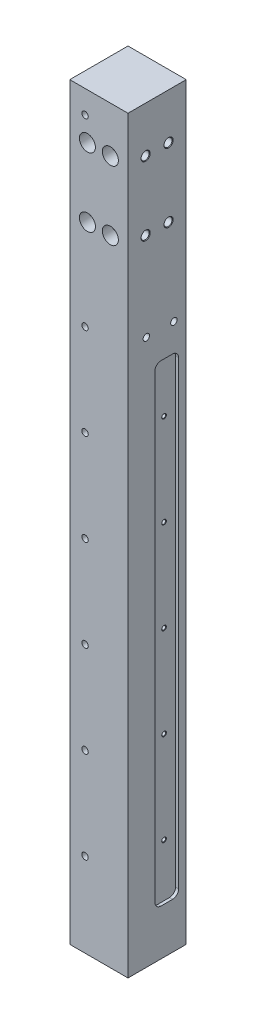
SolidWorks part; units mm, degrees
material "AISI 1045 Steel, cold drawn"
ref_plane "Front Plane" through (0, 0, 0) normal (0, 0, 1) x (1, 0, 0)
ref_plane "Top Plane" through (0, 0, 0) normal (0, 1, 0) x (1, 0, 0)
ref_plane "Right Plane" through (0, 0, 0) normal (1, 0, 0) x (0, 0, -1)
sketch "Sketch1" plane through (0, 0, 0) normal (0, 1, 0) x (1, 0, 0)
  line L1 (19.05, -19.05) -> (-19.05, -19.05)
  line L2 (19.05, -19.05) -> (19.05, 19.05)
  line L3 (19.05, 19.05) -> (-19.05, 19.05)
  line L4 (-19.05, -19.05) -> (-19.05, 19.05)
  line L5 (19.05, -19.05) -> (-19.05, 19.05) construction
  line L6 (19.05, 19.05) -> (-19.05, -19.05) construction
  point P0 (0, 0)
  dimension "D1" = 38.1
extrude "Boss-Extrude1" add sketch "Sketch1" along normal blind 490
ref_plane "Plane1" through (0, 0, 0) normal (-0.7071, 0, -0.7071) x (-0.7071, 0, 0.7071)
hole_wizard "CBORE for M5 SBHCS1" positions "Sketch2" profile "Sketch3" counterbore size "M5" standard "ANSI Metric" end condition through all
sketch "Sketch2" plane through (-19.05, 0, 0) normal (-1, 0, 0) x (0, 0, 1)
  line L0 (-7.5, 415) -> (7.5, 415) construction
  line L2 (-19.05, 490) -> (19.05, 490) construction
  line L3 (-7.5, 460) -> (7.5, 460) construction
  point P0 (-7.5, 415)
  point P2 (7.5, 415)
  point P9 (0, 415)
  point P13 (-7.5, 460)
  point P15 (7.5, 460)
  point P23 (0, 460)
  dimension "D1" = 75
  dimension "D2" = 15
  dimension "D3" = 30
sketch "Sketch3" plane through (-19.05, 415, -7.5) normal (0, 1, 0) x (0, 0, 1)
  line L0 (0, 0) -> (0, 38.1)
  line L1 (2.65, 37.75) -> (3, 38.1)
  line L2 (2.65, 37.75) -> (2.65, 32.85)
  line L3 (2.65, 32.85) -> (5.25, 32.85)
  line L4 (5.25, 32.85) -> (5.25, 0)
  line L5 (5.25, 0) -> (0, 0)
  line L11 (0, -6.35) -> (0, 107.95) construction
  line L12 (3, 38.1) -> (0, 38.1)
  line L13 (-2.65, 37.75) -> (-3, 38.1) construction
  dimension "Thru Hole Dia." = 5.3
  dimension "Thru Hole Depth" = 38.1
  dimension "C'Bore Dia." = 10.5
  dimension "C'Bore Depth" = 32.85
  dimension "Far C'Sink Dia." = 6
  dimension "Far C'Sink Angle" = 90
hole_wizard "M5x0.8 Tapped Hole1" positions "Sketch4" profile "Sketch6" tap size "M5x0.8" standard "ANSI Metric"
sketch "Sketch4" plane through (-19.05, 0, 0) normal (-1, 0, 0) x (0, 0, 1)
  line L0 (-19.05, 490) -> (19.05, 490) construction
  line L1 (19.05, 490) -> (19.05, 0) construction
  line L2 (9.05, 475) -> (9.05, 415) construction
  point P0 (9.05, 475)
  point P13 (9.05, 415)
  point P14 (9.05, 355)
  point P15 (9.05, 295)
  point P16 (9.05, 235)
  point P17 (9.05, 175)
  point P18 (9.05, 115)
  point P19 (9.05, 55)
  dimension "D1" = 15
  dimension "D2" = 10
  dimension "D4" = 60
  dimension "D3" = 8
sketch "Sketch6" plane through (-19.05, 475, 9.05) normal (0, 1, 0) x (0, 0, 1)
  line L0 (0, 0) -> (0, 9.6618)
  line L1 (0, 9.6618) -> (2.1, 8.4)
  line L2 (2.1, 8.4) -> (2.1, 0)
  line L5 (2.1, 0) -> (0, 0)
  line L10 (0, 9.6618) -> (-2.1, 8.4) construction
  line L11 (0, -6.35) -> (0, 107.95) construction
  dimension "Tap Drill Dia." = 4.2
  dimension "Tap Drill Depth" = 8.4
  dimension "Drill Angle" = 118
cosmetic thread "Hole Thread1" parameters "D1"=6, "D2"=5
cosmetic thread "Hole Thread2" parameters "D1"=6, "D2"=5
cosmetic thread "Hole Thread3" parameters "D1"=6, "D2"=5
cosmetic thread "Hole Thread4" parameters "D1"=6, "D2"=5
cosmetic thread "Hole Thread5" parameters "D1"=6, "D2"=5
cosmetic thread "Hole Thread6" parameters "D1"=6, "D2"=5
cosmetic thread "Hole Thread7" parameters "D1"=6, "D2"=5
hole_wizard "M5x0.8 Tapped Hole3" positions "Sketch9" profile "Sketch10" tap size "M5x0.8" standard "ANSI Metric"
sketch "Sketch9" plane through (19.05, 0, 0) normal (1, 0, 0) x (0, 0, -1)
  line L0 (10.95, 357) -> (-7.05, 357) construction
  line L2 (-19.05, 490) -> (-19.05, 0) construction
  line L3 (-19.05, 490) -> (19.05, 490) construction
  point P0 (-7.05, 357)
  point P2 (10.95, 357)
  point P9 (1.95, 357)
  dimension "D1" = 18
  dimension "D2" = 21
  dimension "D3" = 133
sketch "Sketch10" plane through (19.05, 357, 7.05) normal (0, 1, 0) x (0, 0, -1)
  line L0 (0, 0) -> (0, 7.6618)
  line L1 (0, 7.6618) -> (2.1, 6.4)
  line L2 (2.1, 6.4) -> (2.1, 0)
  line L5 (2.1, 0) -> (0, 0)
  line L10 (0, 7.6618) -> (-2.1, 6.4) construction
  line L11 (0, -6.35) -> (0, 107.95) construction
  dimension "Tap Drill Dia." = 4.2
  dimension "Tap Drill Depth" = 6.4
  dimension "Drill Angle" = 118
cosmetic thread "Hole Thread10" parameters "D1"=4, "D2"=5
cosmetic thread "Hole Thread11" parameters "D1"=4, "D2"=5
sketch "Sketch11" plane through (19.05, 0, 0) normal (1, 0, 0) x (0, 0, -1)
  line L1 (14.05, 339) -> (-1.45, 339)
  line L2 (14.05, 339) -> (14.05, 30)
  line L3 (14.05, 30) -> (-1.45, 30)
  line L4 (-1.45, 339) -> (-1.45, 30)
  line L5 (-19.05, 34.5) -> (19.05, 34.5) construction
  line L6 (-19.05, 490) -> (-19.05, 0) construction
  line L7 (19.05, 490) -> (19.05, 0) construction
  line L8 (-19.05, 0) -> (19.05, 0) construction
  dimension "D1" = 34.5
  dimension "D2" = 4.5
  dimension "D3" = 5
  dimension "D4" = 15.5
  dimension "D5" = 309
extrude "Cut-Extrude1" cut sketch "Sketch11" against normal blind 2
fillet "Fillet1" radius 4 4 edges at (18.05, 30, 1.45) (18.05, 30, -14.05) (18.05, 339, -14.05) (18.05, 339, 1.45)
hole_wizard "M3x0.5 Tapped Hole1" positions "Sketch12" profile "Sketch13" tap size "M3x0.5" standard "ANSI Metric"
sketch "Sketch12" plane through (17.05, 0, 0) normal (1, 0, 0) x (0, 0, -1)
  line L0 (19.05, 490) -> (19.05, 0) construction
  line L1 (-19.05, 0) -> (19.05, 0) construction
  line L2 (6.55, 64.5) -> (6.55, 124.5) construction
  point P0 (6.55, 64.5)
  point P15 (6.55, 124.5)
  point P16 (6.55, 184.5)
  point P17 (6.55, 244.5)
  point P18 (6.55, 304.5)
  dimension "D1" = 12.5
  dimension "D2" = 64.5
  dimension "D4" = 60
  dimension "D3" = 5
sketch "Sketch13" plane through (17.05, 64.5, -6.55) normal (0, 1, 0) x (0, 0, -1)
  line L0 (0, 0) -> (0, 8.2511)
  line L1 (0, 8.2511) -> (1.25, 7.5)
  line L2 (1.25, 7.5) -> (1.25, 0.275)
  line L3 (1.25, 0.275) -> (1.525, 0)
  line L5 (1.525, 0) -> (0, 0)
  line L6 (-1.25, 0.275) -> (-1.525, 0) construction
  line L10 (0, 8.2511) -> (-1.25, 7.5) construction
  line L11 (0, -6.35) -> (0, 107.95) construction
  dimension "Tap Drill Dia." = 2.5
  dimension "Tap Drill Depth" = 7.5
  dimension "Near C'Sink Dia." = 3.05
  dimension "Near C'Sink Angle" = 90
  dimension "Drill Angle" = 118
cosmetic thread "Hole Thread17" parameters "D1"=6, "D2"=3
cosmetic thread "Hole Thread18" parameters "D1"=6, "D2"=3
cosmetic thread "Hole Thread19" parameters "D1"=6, "D2"=3
cosmetic thread "Hole Thread20" parameters "D1"=6, "D2"=3
cosmetic thread "Hole Thread21" parameters "D1"=6, "D2"=3
mirror "Mirror2" about plane through (0, 0, 0) normal (-0.7071, 0, -0.7071) of "M3x0.5 Tapped Hole1", "Fillet1", "Cut-Extrude1", "M5x0.8 Tapped Hole3", "M5x0.8 Tapped Hole1", "CBORE for M5 SBHCS1"
cosmetic thread "Hole Thread22" parameters "D1"=6, "D2"=3
cosmetic thread "Hole Thread23" parameters "D1"=6, "D2"=3
cosmetic thread "Hole Thread24" parameters "D1"=6, "D2"=3
cosmetic thread "Hole Thread25" parameters "D1"=6, "D2"=5
cosmetic thread "Hole Thread26" parameters "D1"=6, "D2"=5
cosmetic thread "Hole Thread27" parameters "D1"=6, "D2"=3
cosmetic thread "Hole Thread28" parameters "D1"=4, "D2"=5
cosmetic thread "Hole Thread29" parameters "D1"=6, "D2"=5
cosmetic thread "Hole Thread30" parameters "D1"=6, "D2"=5
cosmetic thread "Hole Thread31" parameters "D1"=6, "D2"=3
cosmetic thread "Hole Thread32" parameters "D1"=6, "D2"=5
cosmetic thread "Hole Thread33" parameters "D1"=6, "D2"=5
cosmetic thread "Hole Thread34" parameters "D1"=6, "D2"=5
cosmetic thread "Hole Thread35" parameters "D1"=4, "D2"=5
